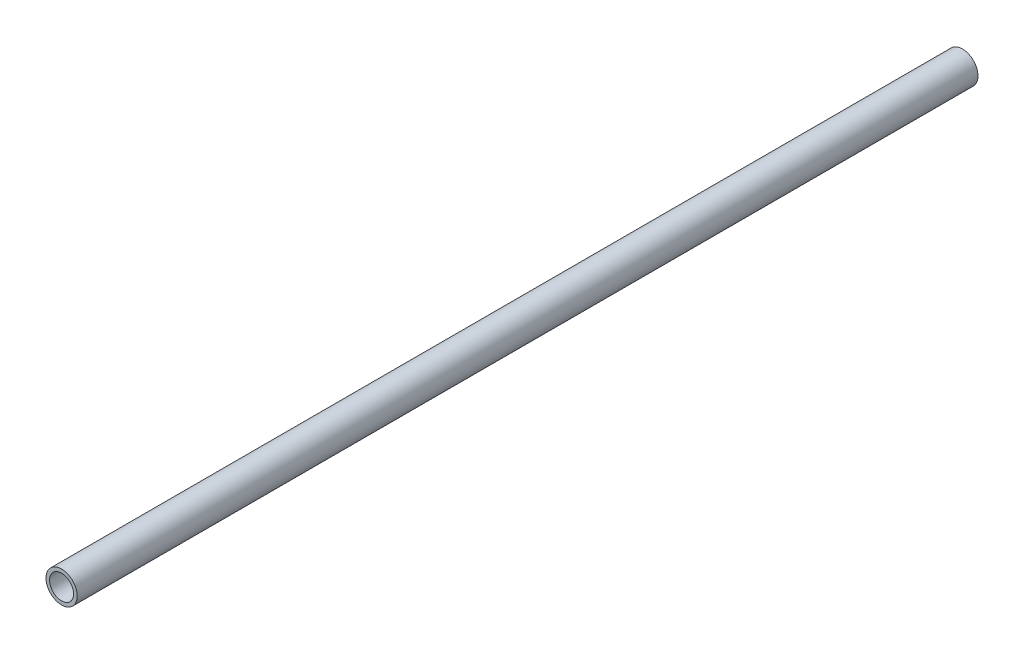
SolidWorks part; units mm, degrees
ref_plane "Front Plane" through (0, 0, 0) normal (0, 0, 1) x (1, 0, 0)
ref_plane "Top Plane" through (0, 0, 0) normal (0, 1, 0) x (1, 0, 0)
ref_plane "Right Plane" through (0, 0, 0) normal (1, 0, 0) x (0, 0, -1)
sketch "Sketch1" plane through (0, 0, 0) normal (0, 0, 1) x (1, 0, 0)
  circle A0 centre (0, 0) radius 16.51
  circle A1 centre (0, 0) radius 12.7
  dimension "D1" = 33.02
  dimension "D2" = 25.4
extrude "Boss-Extrude1" add sketch "Sketch1" along normal blind 952.5
ref_plane "Fitting2" through (0, 0, 952.5) normal (0, 0, 1) x (1, 0, 0)
ref_plane "Fitting1" through (0, 0, 0) normal (0, 0, 1) x (1, 0, 0)
